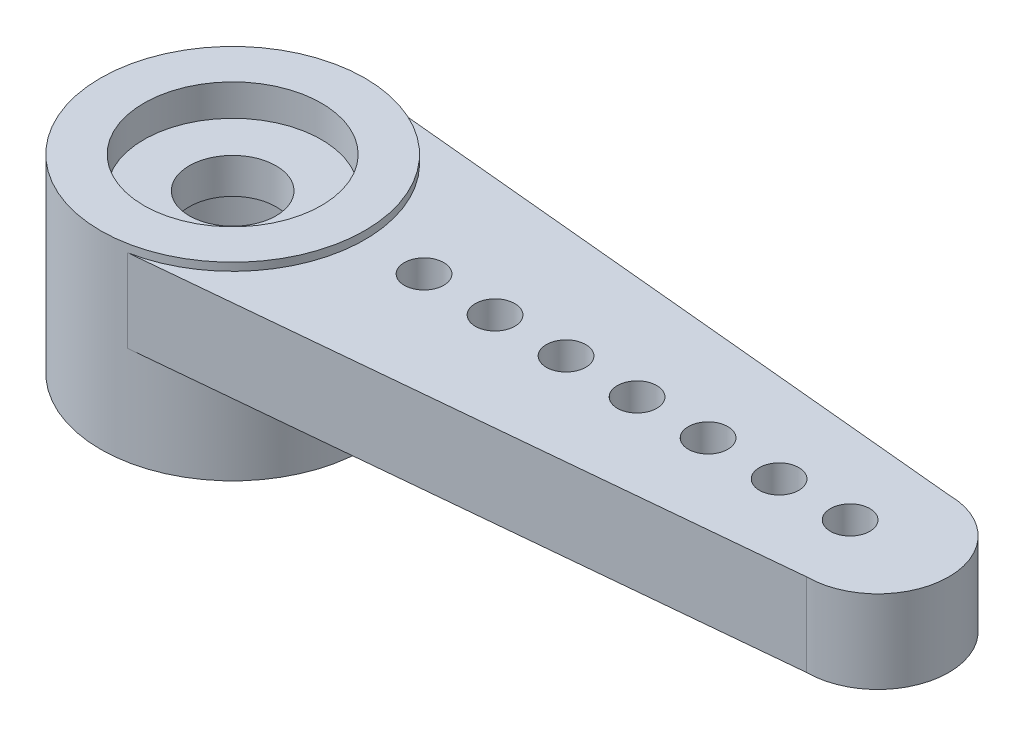
SolidWorks part; units mm, degrees
ref_plane "Plan de face" through (0, 0, 0) normal (0, 0, 1) x (1, 0, 0)
ref_plane "Plan de dessus" through (0, 0, 0) normal (0, 1, 0) x (1, 0, 0)
ref_plane "Plan de droite" through (0, 0, 0) normal (1, 0, 0) x (0, 0, -1)
sketch "Esquisse1" plane through (0, 0, 0) normal (0, 1, 0) x (1, 0, 0)
  line L0 (-7.4, 3.35) -> (8.95, 1.8)
  line L1 (-7.4, -3.35) -> (8.95, -1.8)
  line L2 (-10.75, 0) -> (10.75, 0) construction
  arc A0 (-6.7705, 3.2903) -> (-6.7705, -3.2903) centre (-7.4, 0) ccw
  arc A1 (8.95, -1.8) -> (8.95, 1.8) centre (8.95, 0) ccw
  circle A2 centre (-7.4, 0) radius 1.1
  point P2 (-7.4, 3.35)
  point P3 (8.95, 1.8)
  point P8 (-10.75, 0)
  point P9 (10.75, 0)
  point P12 (0, 0)
  dimension "D1" = 6.7
  dimension "D3" = 3.6
  dimension "D4" = 2.2
  dimension "D2" = 21.5
extrude "Boss.-Extru.1" add sketch "Esquisse1" along normal blind 2.1 contours A0 L2 A2 A1 L0 | L2 A0 L1 A1 A2
sketch "Esquisse2" plane through (0, 2.1, 0) normal (0, 1, 0) x (1, 0, 0)
  arc A0 (-7.4, 3.35) -> (-7.4, -3.35) centre (-7.4, 0) ccw construction
  arc A1 (-7.4, 3.35) -> (-7.4, -3.35) centre (-7.4, 0) ccw
  circle A2 centre (-7.4, 0) radius 2.25
  circle A3 centre (-7.4, 0) radius 3.35
  arc M2 (-7.4, 3.35) -> (-7.4, -3.35) centre (-7.4, 0) ccw
  line M3 (-7.4, -3.35) -> (8.95, -1.8)
  line M5 (8.95, 1.8) -> (-7.4, 3.35)
  dimension "D1" = 1.1
extrude "Boss.-Extru.2" add sketch "Esquisse2" along normal blind 0.2 contours A3 A2 M3 M5 M2 | A3 M5 | A3 M3
sketch "Esquisse4" plane through (0, 2.3, 0) normal (0, 1, 0) x (1, 0, 0)
  circle A0 centre (-7.4, 0) radius 1.1 construction
  circle A1 centre (-7.4, 0) radius 2.25
  circle A2 centre (-7.4, 0) radius 2.25
  circle A3 centre (-7.4, 0) radius 1.1
  dimension "D1" = 0
extrude "Enlèv. mat.-Extru.1" cut sketch "Esquisse4" against normal blind 0.8 contours A2
sketch "Esquisse5" plane through (0, 0, 0) normal (0, -1, 0) x (1, 0, 0)
  circle A0 centre (-7.4, 0) radius 2.25 construction
  circle A1 centre (-7.4, 0) radius 2.25
  circle A2 centre (-7.4, 0) radius 3.35
  circle A4 centre (-7.4, 0) radius 3.35
  dimension "D1" = 0
extrude "Boss.-Extru.3" add sketch "Esquisse5" along normal blind 4.8 from surface at -2.3
sketch "Esquisse6" plane through (0, -2.5, 0) normal (0, -1, 0) x (1, 0, 0)
  circle A0 centre (-7.4, 0) radius 1.1 construction
  circle A1 centre (-7.4, 0) radius 2.25 construction
  circle A2 centre (-7.4, 0) radius 1.1
  circle A3 centre (-7.4, 0) radius 2.25
extrude "Enlèv. mat.-Extru.2" cut sketch "Esquisse6" against normal blind 3.1
sketch "Esquisse7" plane through (0, 2.1, 0) normal (0, 1, 0) x (1, 0, 0)
  line L0 (-4.05, 0) -> (10.75, 0) construction
  arc A0 (-6.7705, -3.2903) -> (-6.7705, 3.2903) centre (-7.4, 0) ccw construction
  arc A1 (8.95, -1.8) -> (8.95, 1.8) centre (8.95, 0) ccw construction
  circle A2 centre (-2.55, 0) radius 0.5
  circle A9 centre (-0.75, 0) radius 0.5
  circle A10 centre (1.05, 0) radius 0.5
  circle A11 centre (2.85, 0) radius 0.5
  circle A12 centre (4.65, 0) radius 0.5
  circle A13 centre (6.45, 0) radius 0.5
  circle A14 centre (8.25, 0) radius 0.5
  point P10 (9.25, 0)
  dimension "D1" = 1
  dimension "D3" = 1.5
  dimension "D2" = 1.5
  dimension "D5" = 1.8
  dimension "D4" = 7
extrude "Enlèv. mat.-Extru.3" cut sketch "Esquisse7" against normal up to next
